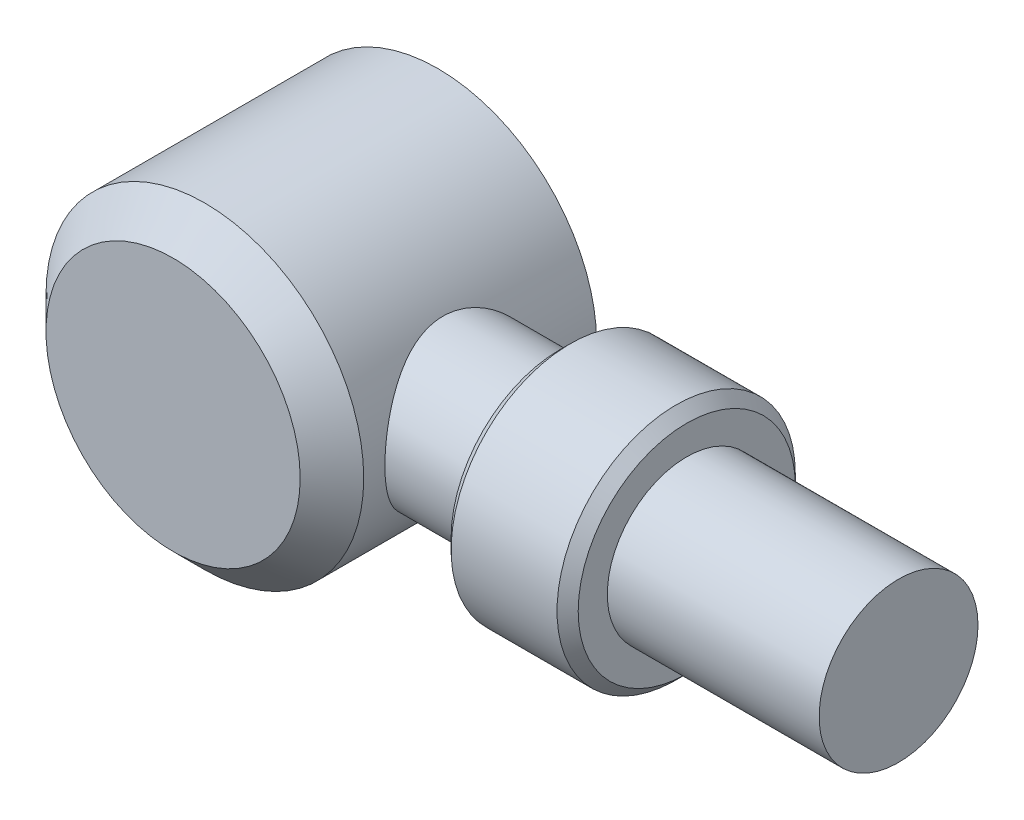
SolidWorks part; units mm, degrees
ref_plane "Ön Düzlem" through (0, 0, 0) normal (0, 0, 1) x (1, 0, 0)
ref_plane "Üst Düzlem" through (0, 0, 0) normal (0, 1, 0) x (1, 0, 0)
ref_plane "Sağ Düzlem" through (0, 0, 0) normal (1, 0, 0) x (0, 0, -1)
sketch "Sketch1" plane through (0, 0, 0) normal (0, 0, 1) x (1, 0, 0)
  circle A0 centre (0, 0) radius 30
  dimension "D1" = 60
extrude "Boss-Extrude1" add sketch "Sketch1" along normal mid plane 50
chamfer "Chamfer1" distance 6 angle 45 1 edges at (30, 0, 25)
ref_plane "Plane1" through (112, 0, 0) normal (1, 0, 0) x (0, 0, -1)
sketch "Sketch2" plane through (112, 0, 0) normal (1, 0, 0) x (0, 0, -1)
  circle A0 centre (0, 0) radius 15
  dimension "D1" = 30
extrude "Boss-Extrude2" add sketch "Sketch2" against normal up to body
ref_plane "Plane2" through (72, 0, 0) normal (1, 0, 0) x (0, 0, -1)
sketch "Sketch3" plane through (72, 0, 0) normal (1, 0, 0) x (0, 0, -1)
  circle A0 centre (0, 0) radius 22.5
  dimension "D1" = 45
extrude "Boss-Extrude3" add sketch "Sketch3" against normal blind 24
chamfer "Chamfer2" distance 2 angle 45 2 edges at (48, 0, -22.5) (72, 0, -22.5)
sketch "Sketch4" plane through (0, 0, -25) normal (0, 0, -1) x (-1, 0, 0)
  circle A0 centre (0, 0) radius 15
  dimension "D1" = 30
extrude "Cut-Extrude1" cut sketch "Sketch4" against normal blind 10
